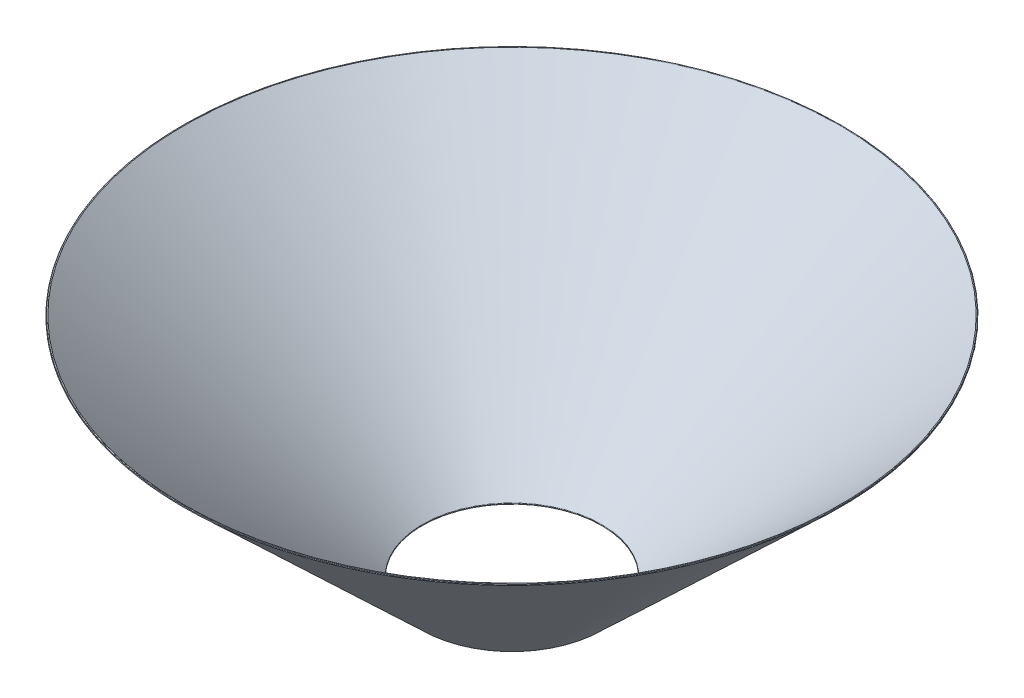
SolidWorks part; units mm, degrees
material "Калифорния"
ref_plane "Спереди" through (0, 0, 0) normal (0, 0, 1) x (1, 0, 0)
ref_plane "Сверху" through (0, 0, 0) normal (0, 1, 0) x (1, 0, 0)
ref_plane "Справа" through (0, 0, 0) normal (1, 0, 0) x (0, 0, -1)
sketch "Эскиз2" plane through (0, 0, 0) normal (0, 0, 1) x (1, 0, 0)
  line L0 (99.4799, 92.1779) -> (27.175, 23.6785)
  line L1 (96.3946, 89.2549) -> (102.8556, 95.3759) construction
  line L2 (27.1674, 23.3958) -> (27.2361, 23.3232)
  line L3 (99.7626, 92.1702) -> (99.8314, 92.0976)
  line L4 (99.8238, 91.8149) -> (27.5189, 23.3155)
  line L5 (0, -32.6177) -> (0, 145.6256) construction
  arc A0 (27.175, 23.6785) -> (27.1674, 23.3958) centre (27.3126, 23.5333) ccw
  arc A1 (27.2361, 23.3232) -> (27.5189, 23.3155) centre (27.3813, 23.4607) ccw
  arc A2 (99.4799, 92.1779) -> (99.7626, 92.1702) centre (99.6174, 92.0327) cw
  arc A3 (99.8314, 92.0976) -> (99.8238, 91.8149) centre (99.6862, 91.9601) cw
  point P12 (27.0298, 23.5409)
  point P15 (27.3737, 23.178)
  point P18 (99.6251, 92.3154)
  point P21 (99.969, 91.9524)
  dimension "D4" = 0.2
  dimension "D1" = 100
  dimension "D2" = 0.5
  dimension "D3" = 0.5
revolve "Повернуть1" add sketch "Эскиз2" angle 360 about L5
